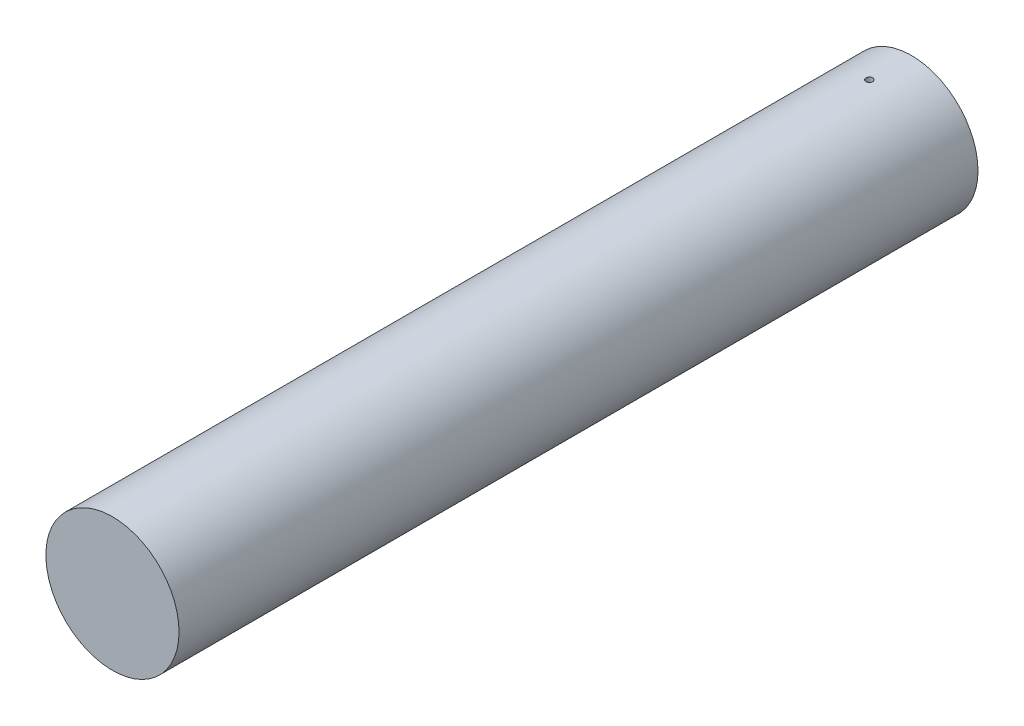
SolidWorks part; units mm, degrees
material "Lega 1060"
ref_plane "Piano frontale" through (0, 0, 0) normal (0, 0, 1) x (1, 0, 0)
ref_plane "Piano superiore" through (0, 0, 0) normal (0, 1, 0) x (1, 0, 0)
ref_plane "Piano destro" through (0, 0, 0) normal (1, 0, 0) x (0, 0, -1)
sketch "Schizzo1" plane through (0, 0, 0) normal (0, 0, 1) x (1, 0, 0)
  circle A0 centre (0, 0) radius 100
  dimension "D1" = 200
extrude "Estrusione-Estrusione1" add sketch "Schizzo1" along normal blind 1200
sketch "Schizzo2" plane through (0, 0, 0) normal (0, 1, 0) x (1, 0, 0)
  circle A0 centre (0, -63.2187) radius 5
  dimension "D1" = 10
extrude "Taglio-Estrusione1" cut sketch "Schizzo2" against normal through all both and the other way through all
